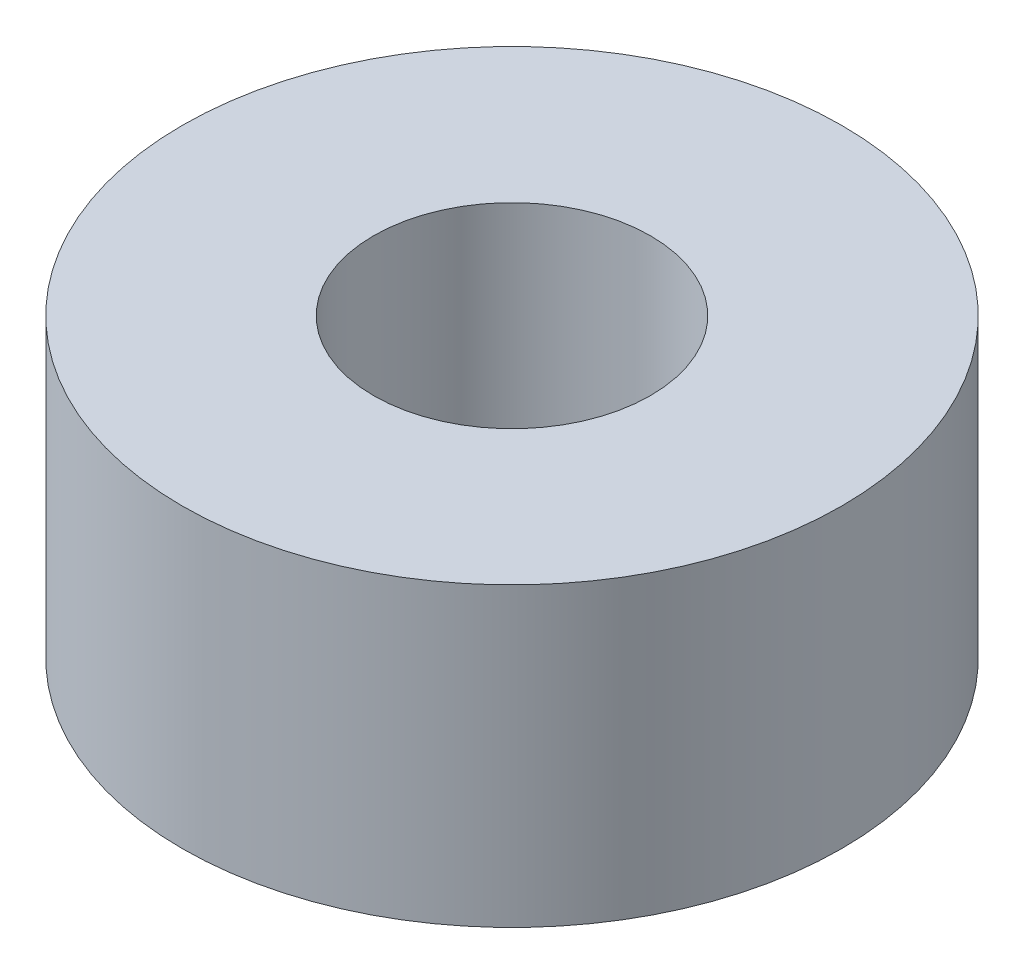
SolidWorks part; units mm, degrees
material "ABS"
ref_plane "Front Plane" through (0, 0, 0) normal (0, 0, 1) x (1, 0, 0)
ref_plane "Top Plane" through (0, 0, 0) normal (0, 1, 0) x (1, 0, 0)
ref_plane "Right Plane" through (0, 0, 0) normal (1, 0, 0) x (0, 0, -1)
sketch "Sketch1" plane through (0, 0, 0) normal (0, 1, 0) x (1, 0, 0)
  circle A0 centre (0, 0) radius 2.1
  circle A1 centre (0, 0) radius 5
  dimension "D1" = 10
  dimension "D2" = 4.2
extrude "Boss-Extrude1" add sketch "Sketch1" along normal blind 4.5
